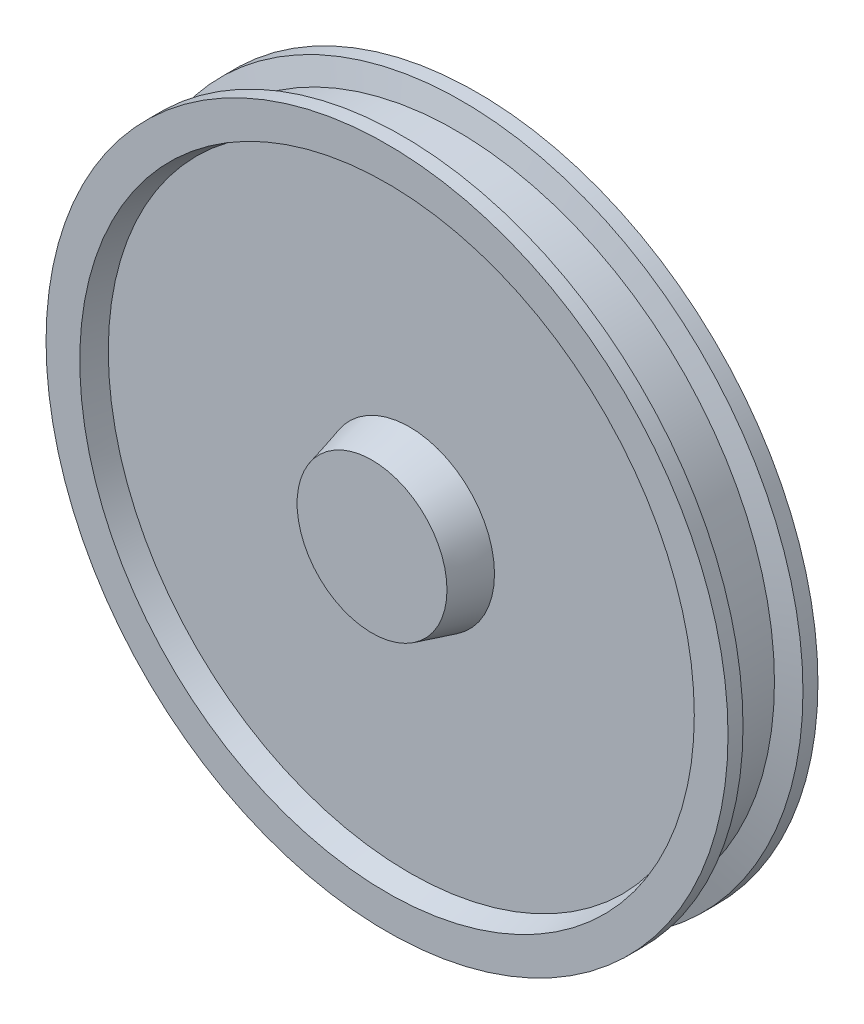
SolidWorks part; units mm, degrees
material "1060 Alloy"
ref_plane "Front Plane" through (0, 0, 0) normal (0, 0, 1) x (1, 0, 0)
ref_plane "Top Plane" through (0, 0, 0) normal (0, 1, 0) x (1, 0, 0)
ref_plane "Right Plane" through (0, 0, 0) normal (1, 0, 0) x (0, 0, -1)
sketch "Sketch1" plane through (0, 0, 0) normal (1, 0, 0) x (0, 0, -1)
  line L0 (-1000, 0) -> (49000, 0) construction
  line L29 (-80, 0) -> (80, 0)
  line L30 (80, 0) -> (80, 100)
  line L31 (80, 100) -> (30, 113.3975)
  line L32 (30, 113.3975) -> (30, 401.9615)
  line L33 (30, 401.9615) -> (60, 410)
  line L34 (60, 410) -> (60, 455)
  line L37 (31.9615, 425) -> (-31.9615, 425)
  line L38 (-31.9615, 425) -> (-40, 455)
  line L39 (-40, 455) -> (-60, 455)
  line L40 (-60, 455) -> (-60, 410)
  line L41 (-60, 410) -> (-30, 401.9615)
  line L42 (-30, 401.9615) -> (-30, 113.3975)
  line L43 (-30, 113.3975) -> (-80, 100)
  line L44 (-80, 100) -> (-80, 0)
  line L45 (31.9615, 425) -> (40, 455)
  line L46 (40, 455) -> (60, 455)
  point P18 (0, 0)
  point P23 (45, 405.9808)
  point P24 (0, 425)
  dimension "D1" = 160
  dimension "D2" = 60
  dimension "D3" = 105
  dimension "D4" = 200
  dimension "D5" = 120
  dimension "D6" = 105
  dimension "D7" = 20
  dimension "D8" = 910
  dimension "D9" = 30
  dimension "D10" = 105
  dimension "D11" = 45
revolve "Revolve1" add sketch "Sketch1" angle 360 about L0
